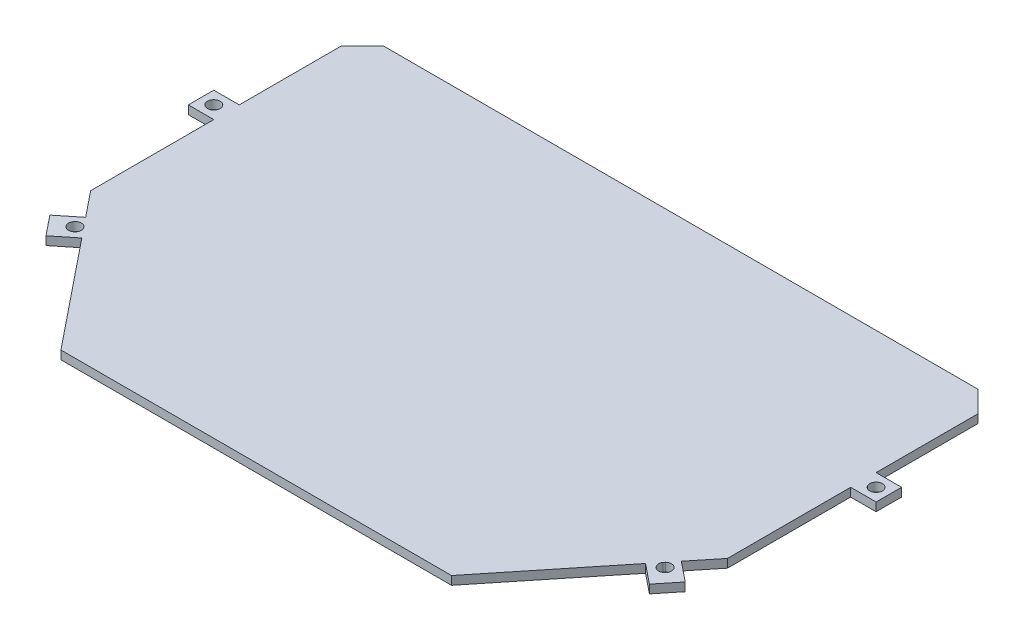
SolidWorks part; units mm, degrees
ref_plane "Front" through (0, 0, 0) normal (0, 0, 1) x (1, 0, 0)
ref_plane "Top" through (0, 0, 0) normal (0, 1, 0) x (1, 0, 0)
ref_plane "Right" through (0, 0, 0) normal (1, 0, 0) x (0, 0, -1)
sketch "Sketch1" plane through (0, 0, 0) normal (0, 1, 0) x (1, 0, 0)
  line L0 (-75, 35) -> (75, 35)
  line L1 (75, 35) -> (75, -29)
  line L2 (75, -29) -> (46, -65)
  line L3 (46, -65) -> (-46, -65)
  line L4 (-46, -65) -> (-75, -29)
  line L5 (-75, -29) -> (-75, 35)
  dimension "D1" = 75
  dimension "D2" = 75
  dimension "D3" = 35
  dimension "D4" = 29
  dimension "D6" = 36
  dimension "D7" = 29
  dimension "D8" = 29
extrude "Extrude1" add sketch "Sketch1" along normal blind 2
sketch "Sketch2" plane through (0, 2, 0) normal (0, 1, 0) x (1, 0, 0)
  line L0 (-38.5, 55) -> (38.5, 55)
  circle A0 centre (0, 0) radius 85
  dimension "D1" = 38.5
  dimension "D4" = 170
  dimension "D2" = 38.5
  dimension "D3" = 55
sketch "Sketch3" plane through (0, 2, 0) normal (0, 1, 0) x (1, 0, 0)
  line L0 (75, 6) -> (81, 6)
  line L1 (75, -29) -> (75, 35) construction
  line L2 (81, 6) -> (81, 0)
  line L3 (81, 0) -> (75, 0)
  line L4 (75, 0) -> (75, 6)
  line L10 (75, 35) -> (-75, 35) construction
  line L12 (70.1522, -35.018) -> (74.8247, -38.782)
  line L13 (70.1522, -35.018) -> (66.3882, -39.6905)
  line L14 (74.8247, -38.782) -> (71.0607, -43.4545)
  line L15 (66.3882, -39.6905) -> (71.0607, -43.4545)
  line L16 (46, -65) -> (75, -29) construction
  circle A0 centre (69.4965, -38.1962) radius 1.5
  circle A1 centre (78, 3) radius 1.5
  line M4 (46, -65) -> (75, -29)
  line M5 (75, -29) -> (75, 35)
  dimension "D11" = 3
  dimension "D12" = 3
  dimension "D1" = 6
  dimension "D2" = 29
  dimension "D3" = 6
  dimension "D4" = 3
  dimension "D5" = 3
  dimension "D6" = 6
  dimension "D7" = 6
  dimension "D8" = 69.4965
  dimension "D9" = 38.1962
  dimension "D10" = 32.5
extrude "Extrude2" add sketch "Sketch3" against normal up to surface (2 mm away) contours L3 L2 L0 A1 M5 | A0 L15 L14 L12 M4 up to face at (0, 0, 19.6667)
chamfer "Chamfer2" distance 5 angle 45 2 edges at (-75, 1, -35) (75, 1, -35)
mirror "Mirror1" about plane through (0, 0, 0) normal (1, 0, 0) of "Extrude2"
